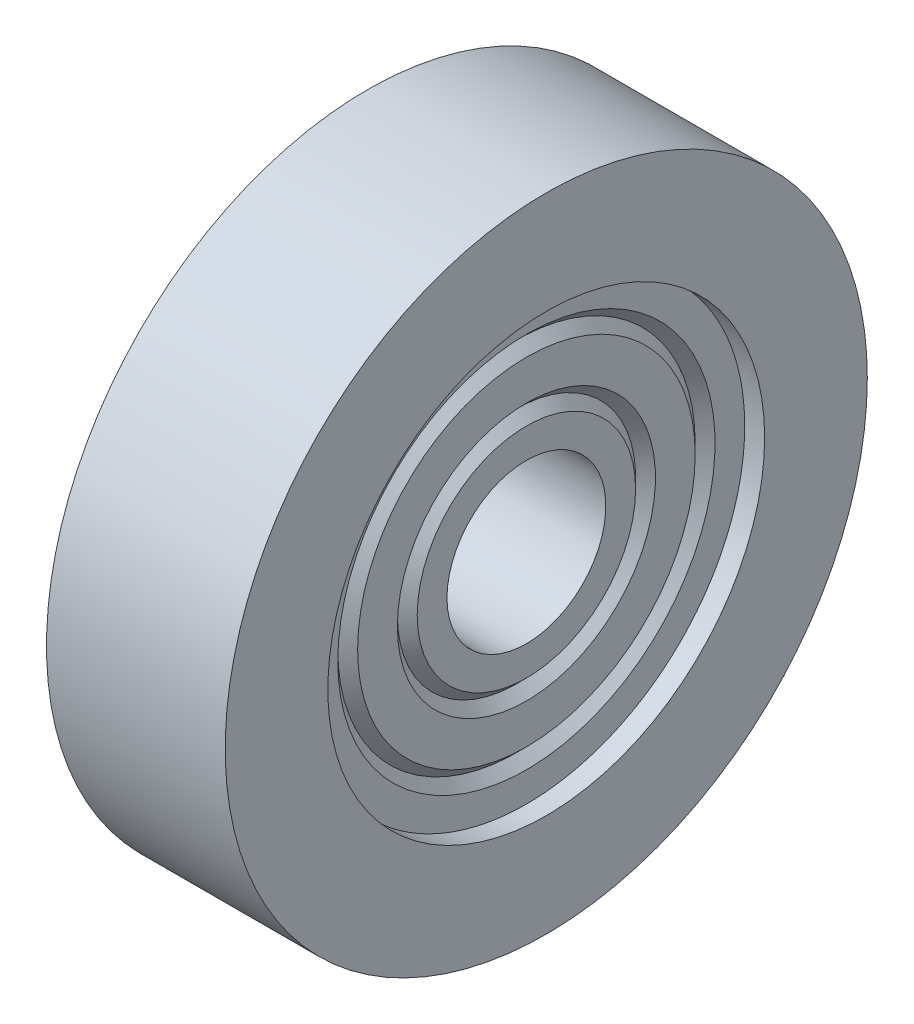
SolidWorks part; units mm, degrees
ref_plane "Face" through (0, 0, 0) normal (0, 0, 1) x (1, 0, 0)
ref_plane "Dessus" through (0, 0, 0) normal (0, 1, 0) x (1, 0, 0)
ref_plane "Droite" through (0, 0, 0) normal (1, 0, 0) x (0, 0, -1)
sketch "Esquisse1" plane through (0, 0, 0) normal (0, 0, 1) x (1, 0, 0)
  line L0 (0, 0) -> (3.5, 0) construction
  line L1 (-3.5, 4) -> (3.5, 4)
  line L2 (3.5, 4) -> (3.5, 5.5)
  line L3 (3.5, 5.5) -> (3, 6)
  line L4 (3, 6) -> (3.5, 6.5)
  line L5 (3.5, 6.5) -> (3.5, 8.5)
  line L6 (3.5, 8.5) -> (3, 9)
  line L7 (3, 9) -> (3.5, 9.5)
  line L8 (3.5, 9.5) -> (3.5, 11)
  line L9 (3.5, 11) -> (-3.5, 11)
  line L10 (-3.5, 11) -> (-3.5, 9.5)
  line L11 (-3.5, 9.5) -> (-3, 9)
  line L12 (-3, 9) -> (-3.5, 8.5)
  line L13 (-3.5, 8.5) -> (-3.5, 6.5)
  line L14 (-3.5, 6.5) -> (-3, 6)
  line L15 (-3, 6) -> (-3.5, 5.5)
  line L16 (-3.5, 5.5) -> (-3.5, 4)
  line L17 (0, 0) -> (0, 4) construction
  dimension "D1" = 7
  dimension "D2" = 4
  dimension "D3" = 11
  dimension "D4" = 1.5
  dimension "D5" = 1.5
  dimension "D6" = 1
  dimension "D7" = 1
  dimension "D8" = 1.5
  dimension "D9" = 1.5
  dimension "D10" = 1
  dimension "D11" = 1
  dimension "D12" = 0.5
  dimension "D13" = 0.5
  dimension "D14" = 0.5
  dimension "D15" = 0.5
  dimension "D16" = 0.5
  dimension "D17" = 0.5
  dimension "D18" = 0.5
  dimension "D19" = 0.5
revolve "Base-Révolution" add sketch "Esquisse1" angle 360 about L0
sketch "Esquisse2" plane through (0, 0, 0) normal (1, 0, 0) x (0, 0, -1)
  circle A0 centre (0, 0) radius 11 construction
  circle A1 centre (0, 0) radius 16.17
  circle A2 centre (0, 0) radius 11
  dimension "D1" = 32.34
extrude "Boss.-Extru.1" add sketch "Esquisse2" along normal mid plane 9 separate body
